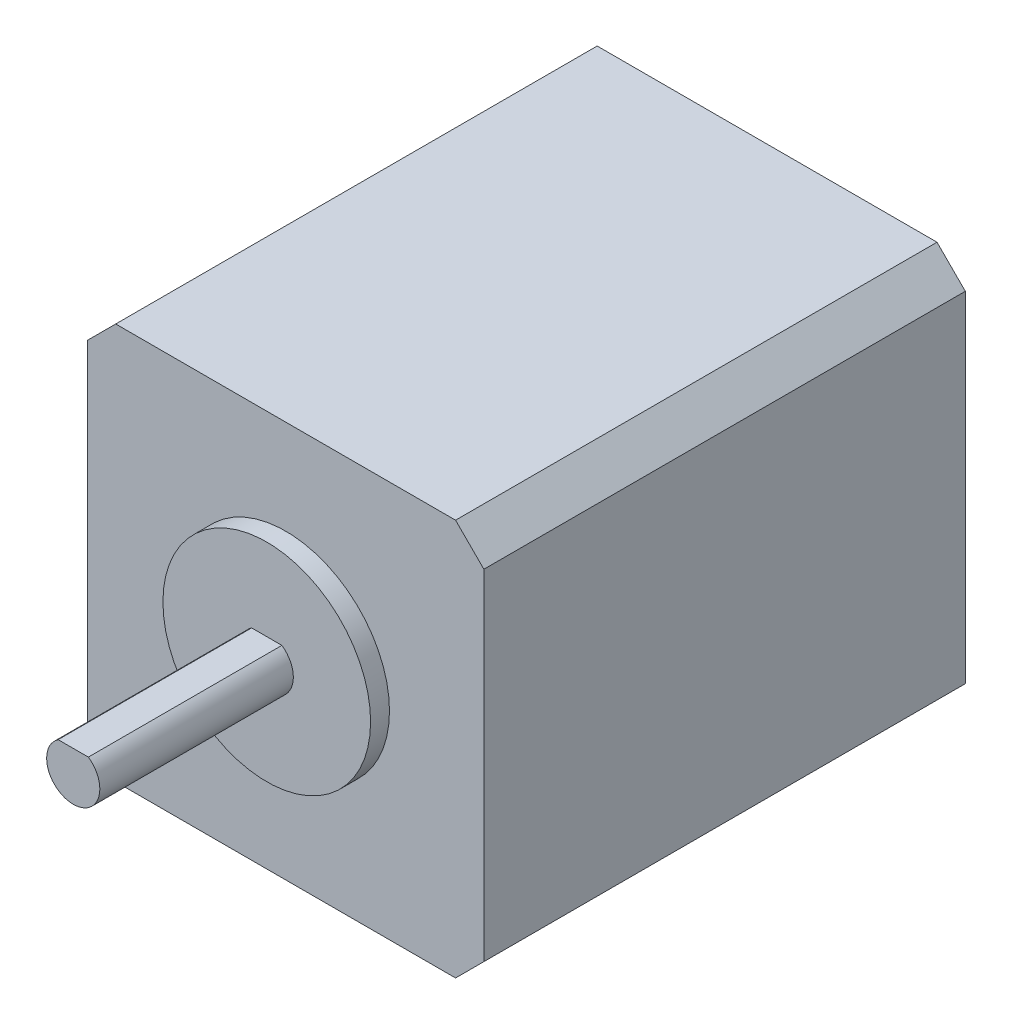
SolidWorks part; units mm, degrees
ref_plane "前视基准面" through (0, 0, 0) normal (0, 0, 1) x (1, 0, 0)
ref_plane "上视基准面" through (0, 0, 0) normal (0, 1, 0) x (1, 0, 0)
ref_plane "右视基准面" through (0, 0, 0) normal (1, 0, 0) x (0, 0, -1)
other "Configuration Table"
sketch "草图1" plane through (0, 0, 0) normal (0, 0, 1) x (1, 0, 0)
  line L1 (-21, -21) -> (21, -21)
  line L2 (-21, -21) -> (-21, 21)
  line L3 (-21, 21) -> (21, 21)
  line L4 (21, -21) -> (21, 21)
  line L5 (-21, -21) -> (21, 21) construction
  line L6 (-21, 21) -> (21, -21) construction
  point P0 (0, 0)
  dimension "D1" = 42
  dimension "D2" = 42
extrude "凸台-拉伸1" add sketch "草图1" along normal blind 51
sketch "草图2" plane through (0, 0, 51) normal (0, 0, 1) x (1, 0, 0)
  circle A0 centre (0, 0) radius 11
  dimension "D1" = 22
extrude "凸台-拉伸2" add sketch "草图2" along normal blind 2
sketch "草图3" plane through (0, 0, 53) normal (0, 0, 1) x (1, 0, 0)
  line L0 (-1.6018, 2.3158) -> (1.6018, 2.3158)
  arc A0 (-1.6018, 2.3158) -> (1.6018, 2.3158) centre (0, 0) ccw
  point P5 (0, 2.8158)
  dimension "D1" = 0.5
extrude "凸台-拉伸3" add sketch "草图3" along normal blind 20.5
chamfer "倒角1" distance 3 angle 45 4 edges at (21, -21, 25.5) (-21, -21, 25.5) (-21, 21, 25.5) (21, 21, 25.5)
